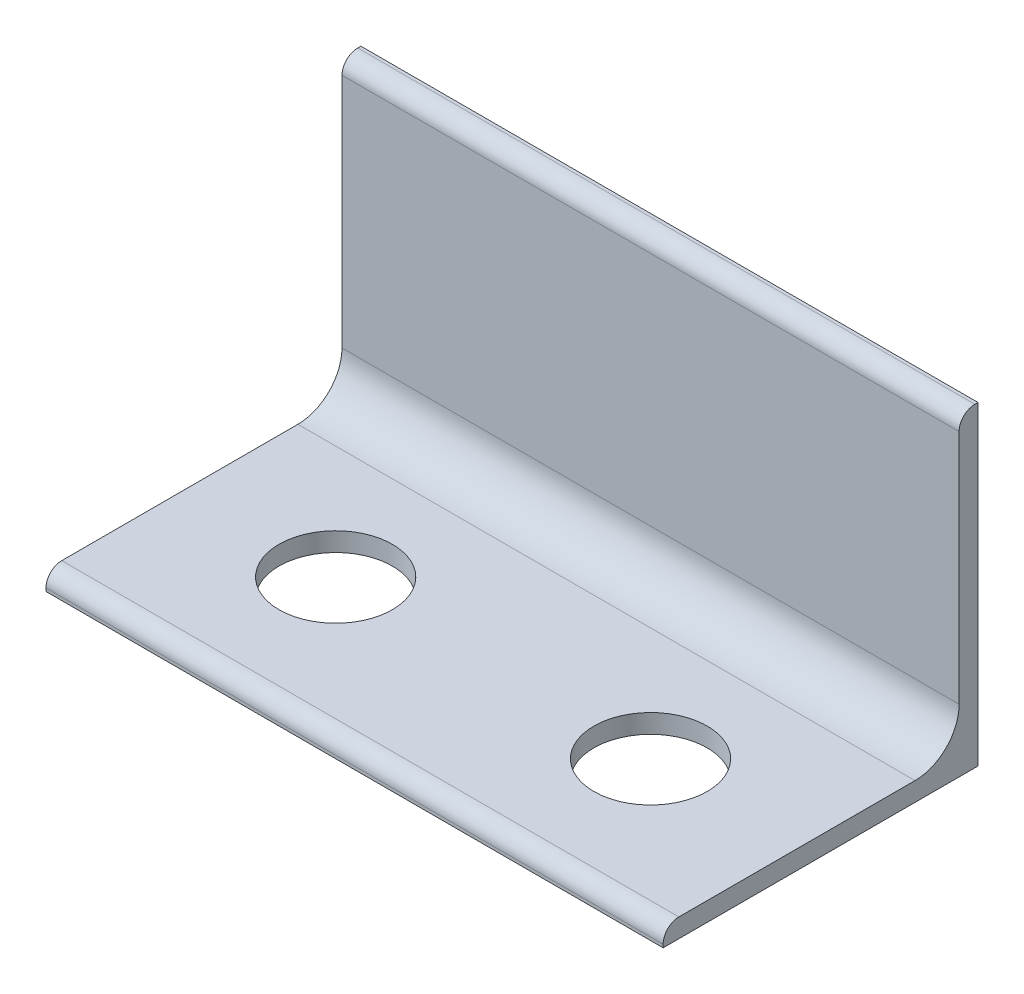
SolidWorks part; units mm, degrees
other "Connection Feature"
ref_plane "Front Plane" through (0, 0, 0) normal (0, 0, 1) x (1, 0, 0)
ref_plane "Top Plane" through (0, 0, 0) normal (0, 1, 0) x (1, 0, 0)
ref_plane "Right Plane" through (0, 0, 0) normal (1, 0, 0) x (0, 0, -1)
sketch "Sketch1" plane through (0, 0, 0) normal (0, 0, 1) x (1, 0, 0)
  line L0 (0, 0) -> (98, 0)
  point P4 (0, 0)
  dimension "l" = 98
other "Angles equal 50 X 50 X 3(1)"
ref_plane "Plane4" through (0, 25, 25) normal (1, 0, 0) x (0, 1, 0)
sketch "Sketch14" plane through (0, 25, 25) normal (1, 0, 0) x (0, 1, 0)
  line L0 (-25, 25) -> (-25, -25)
  line L1 (-25, -25) -> (25, -25) construction
  line L2 (-25, -25) -> (-25, 25) construction
  line L3 (-25, 25) -> (25, 25) construction
  line L4 (25, -25) -> (25, 25) construction
  line L5 (-25, -25) -> (25, 25) construction
  line L6 (-25, 25) -> (25, -25) construction
  line L7 (-25, -25) -> (25, -25)
  line L8 (25, -25) -> (25, -24.5)
  line L9 (22.5, -22) -> (-15, -22)
  line L10 (-22, -15) -> (-22, 22.5)
  line L11 (-24.5, 25) -> (-25, 25)
  arc A0 (-15, -22) -> (-22, -15) centre (-15, -15) cw
  arc A1 (-22, 22.5) -> (-24.5, 25) centre (-24.5, 22.5) ccw
  arc A2 (25, -24.5) -> (22.5, -22) centre (22.5, -24.5) ccw
  point P0 (0, 0)
  point P13 (-22, 25)
  point P16 (25, -22)
  point P17 (-25, 0)
  point P18 (-25, 25)
  point P19 (0, -25)
  point P20 (-25, -25)
  point P21 (0, 0)
  point P22 (25, -25)
  point P23 (25, 0)
  point P24 (25, 25)
  point P25 (0, 25)
  point P26 (0, 0)
  dimension "r1" = 7
  dimension "r2" = 2.5
  dimension "hxb" = 50
  dimension "t" = 3
sketch "Sketch17" plane through (0, 3, 0) normal (0, 1, 0) x (1, 0, 0)
  line L1 (-27.5, 0) -> (27.5, 0) construction
  line L2 (0, -27.5) -> (0, 27.5) construction
  line L3 (49, -47.5) -> (49, -10) construction
  line L4 (98, -47.5) -> (0, -47.5) construction
  line L5 (98, -10) -> (0, -10) construction
  point P0 (24, -28)
  dimension "Back Mark Distance" = 28
  dimension "Edge Distance" = 24
hole_wizard "Ø18.0 (18) Diameter Hole1" positions "Sketch17" profile "Sketch16" hole size "Ø18.0" standard "ISO" end condition through all
sketch "Sketch16" plane through (24, 3, 28) normal (1, 0, 0) x (0, 0, 1)
  line L0 (0, 0) -> (0, 3)
  line L1 (0, 3) -> (9, 3)
  line L2 (9, 3) -> (9, 0)
  line L5 (9, 0) -> (0, 0)
  line L11 (0, -6.35) -> (0, 107.95) construction
  dimension "Thru Hole Dia." = 18
  dimension "Thru Hole Depth" = 3
pattern_linear "LPattern1" count 2 spacing 50 along (1, 0, 0) of "Ø18.0 (18) Diameter Hole1"
ref_plane "Center Reference Plane" through (49, 0, 0) normal (1, 0, 0) x (0, 0, -1)
